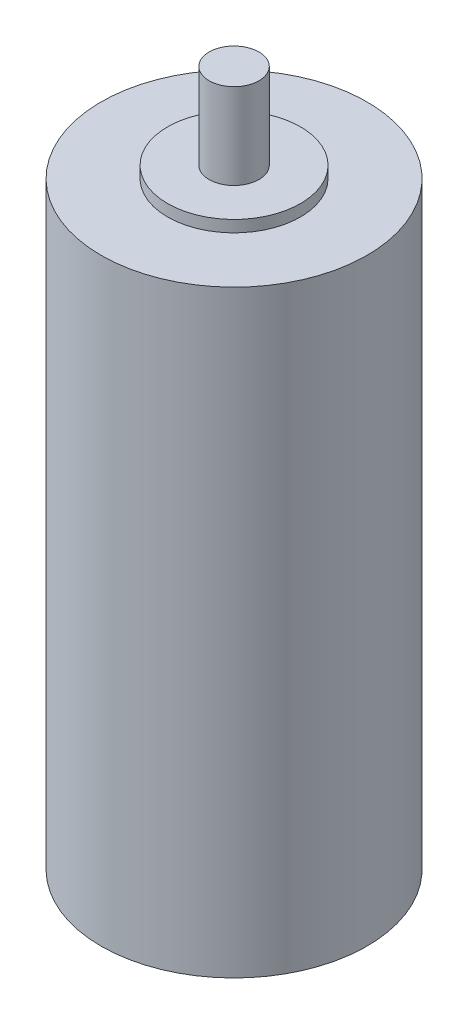
SolidWorks part; units mm, degrees
material "Vanadium"
ref_plane "Plan de face" through (0, 0, 0) normal (0, 0, 1) x (1, 0, 0)
ref_plane "Plan de dessus" through (0, 0, 0) normal (0, 1, 0) x (1, 0, 0)
ref_plane "Plan de droite" through (0, 0, 0) normal (1, 0, 0) x (0, 0, -1)
sketch "Sketch1" plane through (0, 0, 0) normal (0, 1, 0) x (1, 0, 0)
  circle A0 centre (0, 0) radius 16
  dimension "D1" = 32
extrude "Boss-Extrude1" add sketch "Sketch1" along normal blind 72
sketch "Sketch2" plane through (0, 72, 0) normal (0, 1, 0) x (1, 0, 0)
  circle A0 centre (0, 0) radius 8
  dimension "D1" = 16
extrude "Boss-Extrude2" add sketch "Sketch2" along normal blind 1.4
sketch "Sketch4" plane through (0, 72, 0) normal (0, 1, 0) x (1, 0, 0)
  circle A0 centre (0, 0) radius 3
  dimension "D1" = 6
extrude "Boss-Extrude3" add sketch "Sketch4" along normal blind 11.7
ref_point "Point1"
